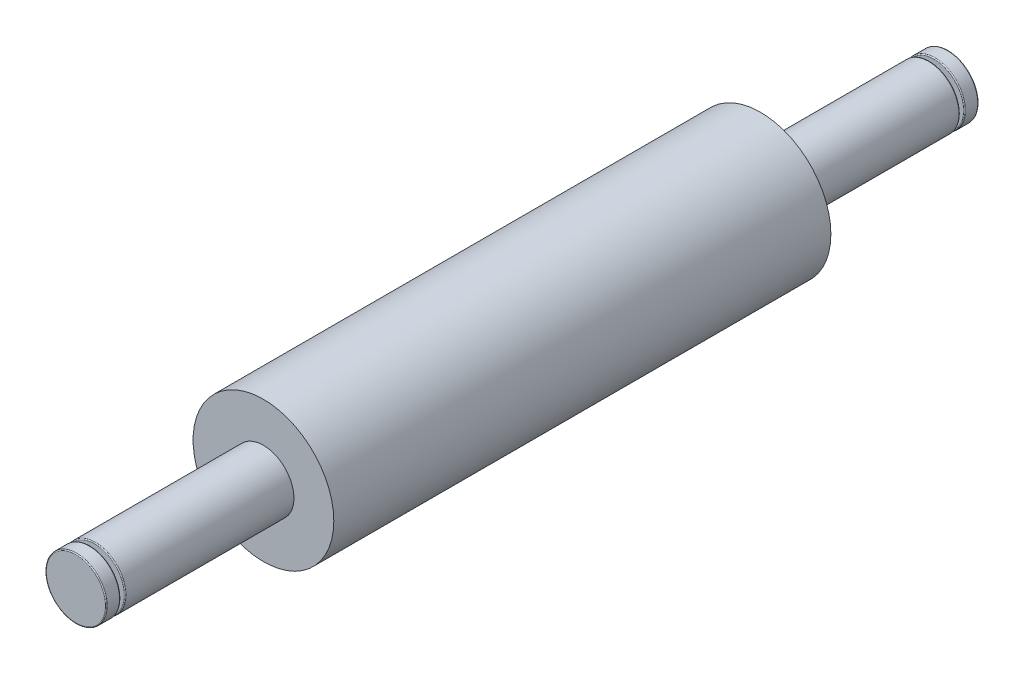
SolidWorks part; units mm, degrees
ref_plane "Front Plane" through (0, 0, 0) normal (0, 0, 1) x (1, 0, 0)
ref_plane "Top Plane" through (0, 0, 0) normal (0, 1, 0) x (1, 0, 0)
ref_plane "Right Plane" through (0, 0, 0) normal (1, 0, 0) x (0, 0, -1)
sketch "Sketch1" plane through (0, 0, 0) normal (0, 0, 1) x (1, 0, 0)
  circle A0 centre (378.1232, 127.241) radius 7.5 construction
  circle A1 centre (378.1232, 127.241) radius 7.5
extrude "Boss-Extrude1" add sketch "Sketch1" against normal blind 53
sketch "Sketch2" plane through (0, 0, 0) normal (0, 0, 1) x (1, 0, 0)
  circle A0 centre (378.1232, 127.241) radius 3.25
  dimension "D1" = 6.5
extrude "Boss-Extrude2" add sketch "Sketch2" along normal blind 18 and the other way blind 71
sketch "Sketch3" plane through (0, 0, 18) normal (0, 0, 1) x (1, 0, 0)
  circle A0 centre (378.1232, 127.241) radius 1.75
  dimension "D1" = 3.5
extrude "Boss-Extrude3" add sketch "Sketch3" along normal blind 0.5 and the other way blind 89.5
sketch "Sketch4" plane through (0, 0, 18.5) normal (0, 0, 1) x (1, 0, 0)
  circle A0 centre (378.1232, 127.241) radius 3.25
  dimension "D1" = 6.5
extrude "Boss-Extrude4" add sketch "Sketch4" along normal blind 1.5
sketch "Sketch5" plane through (0, 0, -71.5) normal (0, 0, -1) x (-1, 0, 0)
  circle A0 centre (-378.1232, 127.241) radius 3.25
  dimension "D1" = 6.5
extrude "Boss-Extrude5" add sketch "Sketch5" along normal blind 1.5
fillet "Fillet1" radius 0.1 4 edges at (381.3732, 127.241, 18.5) (381.3732, 127.241, 18) (381.3732, 127.241, -71) (374.8732, 127.241, -71.5)
fillet "Fillet2" radius 0.1 2 edges at (374.8732, 127.241, -73) (381.3732, 127.241, 20)
